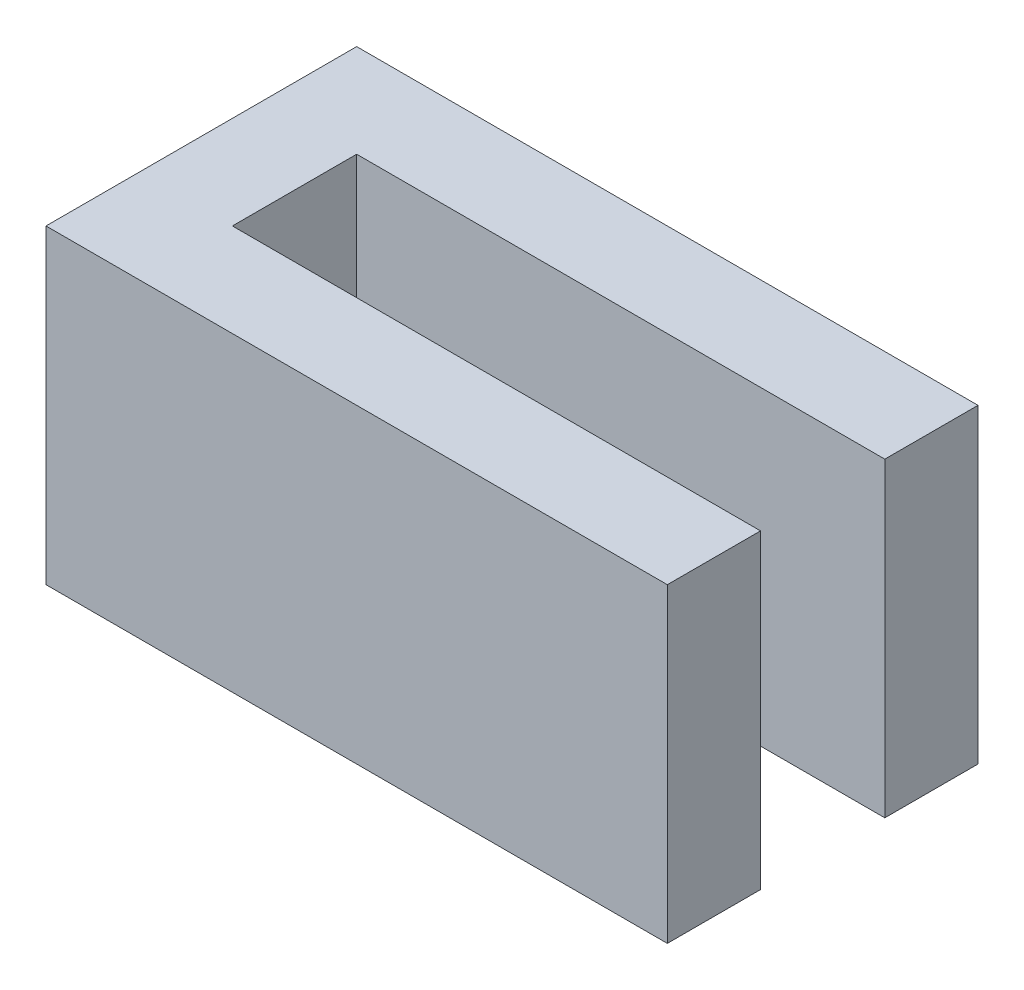
SolidWorks part; units mm, degrees
ref_plane "Front Plane" through (0, 0, 0) normal (0, 0, 1) x (1, 0, 0)
ref_plane "Top Plane" through (0, 0, 0) normal (0, 1, 0) x (1, 0, 0)
ref_plane "Right Plane" through (0, 0, 0) normal (1, 0, 0) x (0, 0, -1)
sketch "Sketch1" plane through (0, 0, 0) normal (0, 1, 0) x (1, 0, 0)
  line L0 (0, 0) -> (100, 0)
  line L1 (100, 0) -> (100, 15)
  line L2 (100, 15) -> (15, 15)
  line L3 (15, 15) -> (15, 35)
  line L4 (15, 35) -> (100, 35)
  line L5 (100, 35) -> (100, 50)
  line L6 (100, 50) -> (0, 50)
  line L7 (0, 50) -> (0, 0)
  dimension "D1" = 50
  dimension "D2" = 100
  dimension "D3" = 15
  dimension "D4" = 15
extrude "Boss-Extrude1" add sketch "Sketch1" along normal blind 50
